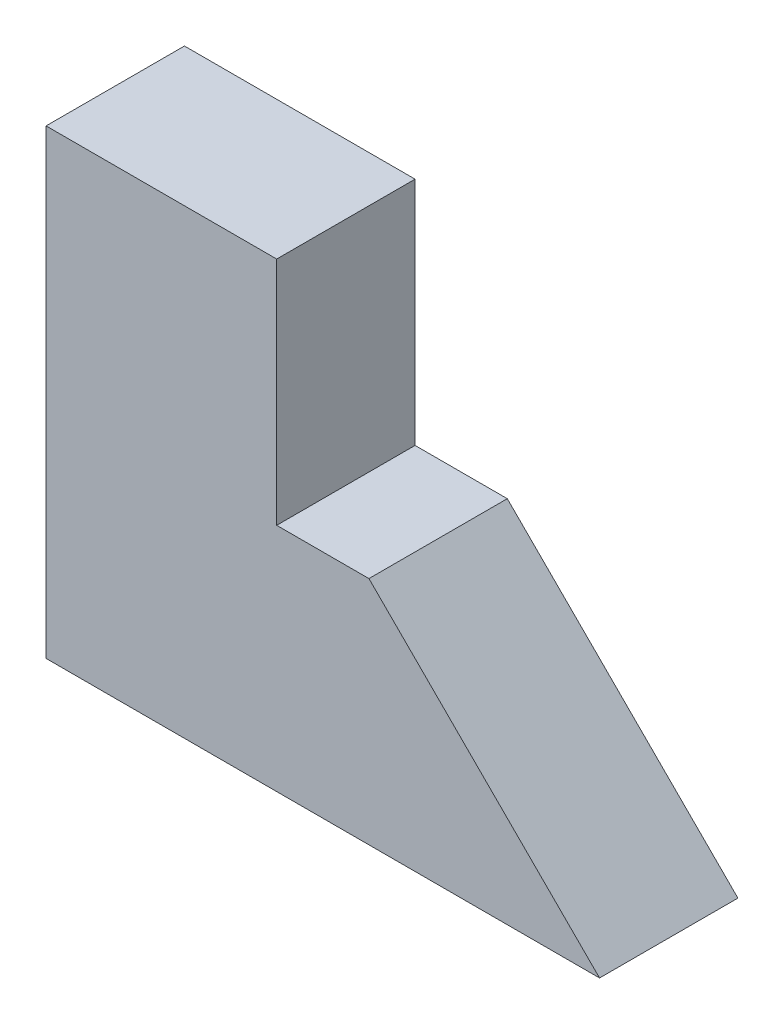
SolidWorks part; units mm, degrees
ref_plane "前视基准面" through (0, 0, 0) normal (0, 0, 1) x (1, 0, 0)
ref_plane "上视基准面" through (0, 0, 0) normal (0, 1, 0) x (1, 0, 0)
ref_plane "右视基准面" through (0, 0, 0) normal (1, 0, 0) x (0, 0, -1)
sketch "草图1" plane through (0, 0, 0) normal (0, 0, 1) x (1, 0, 0)
  line L0 (0, 0) -> (2, 0)
  line L1 (0, 0) -> (0, 5)
  line L2 (0, 5) -> (-5, 5)
  line L3 (-5, 5) -> (-5, -5)
  line L4 (-5, -5) -> (7, -5)
  line L5 (2, 0) -> (7, -5)
extrude "凸台-拉伸1" add sketch "草图1" along normal blind 3
